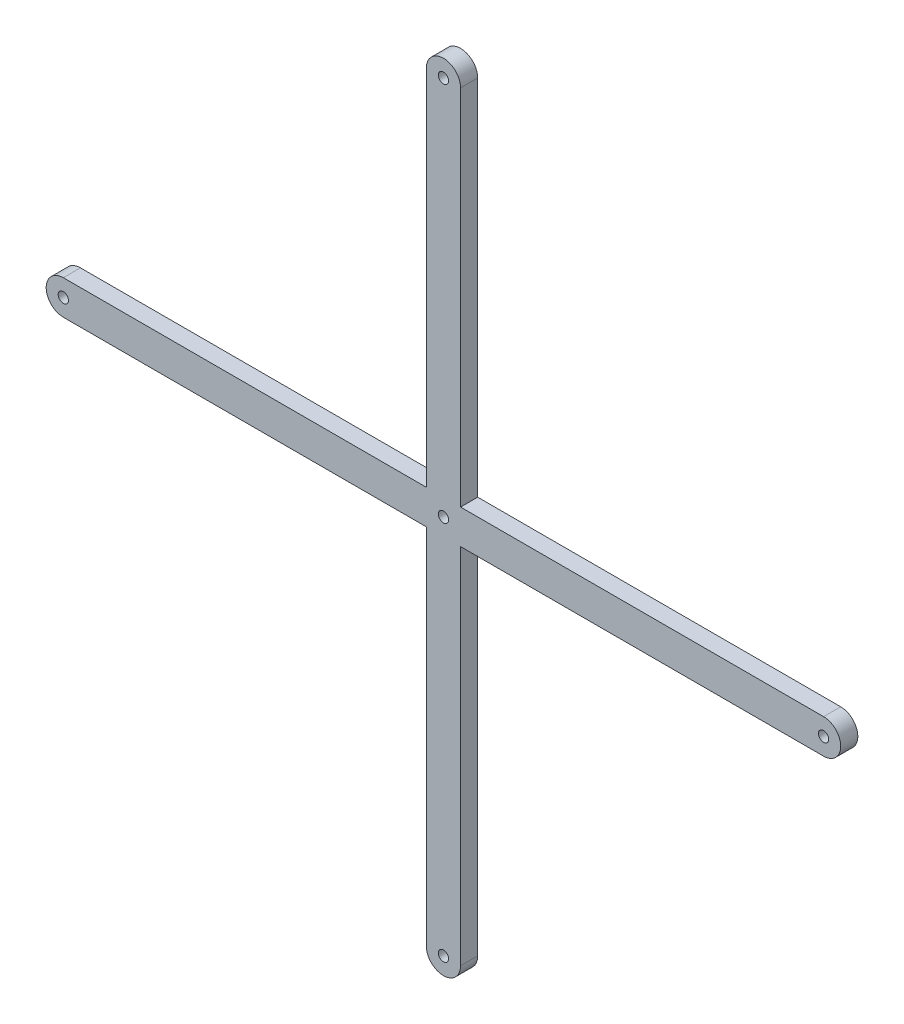
SolidWorks part; units mm, degrees
ref_plane "Front Plane" through (0, 0, 0) normal (0, 0, 1) x (1, 0, 0)
ref_plane "Top Plane" through (0, 0, 0) normal (0, 1, 0) x (1, 0, 0)
ref_plane "Right Plane" through (0, 0, 0) normal (1, 0, 0) x (0, 0, -1)
sketch "Sketch1" plane through (0, 0, 0) normal (0, 0, 1) x (1, 0, 0)
  line L0 (111, 0) -> (-111, 0) construction
  line L1 (5, -5) -> (5, -111)
  line L2 (-5, -5) -> (-5, -111)
  line L3 (0, 111) -> (0, -111) construction
  line L5 (-5, 5) -> (-111, 5)
  line L6 (-5, -5) -> (-111, -5)
  line L7 (5, 5) -> (5, 111)
  line L8 (-5, 5) -> (-5, 111)
  line L9 (5, -5) -> (111, -5)
  line L10 (5, 5) -> (111, 5)
  arc A1 (-5, -111) -> (5, -111) centre (0, -111) ccw
  circle A2 centre (0, 0) radius 1.5
  circle A3 centre (0, -111) radius 1.5
  arc A4 (-111, 5) -> (-111, -5) centre (-111, 0) ccw
  arc A5 (5, 111) -> (-5, 111) centre (0, 111) ccw
  arc A6 (111, -5) -> (111, 5) centre (111, 0) ccw
  circle A7 centre (-111, 0) radius 1.5
  circle A8 centre (0, 111) radius 1.5
  circle A9 centre (111, 0) radius 1.5
  point P3 (0, -55.5)
  point P34 (0, 0)
  point P37 (0, 0)
  dimension "D2" = 4
  dimension "D3" = 3
  dimension "D4" = 3
  dimension "D5" = 5
  dimension "D6" = 4
extrude "Boss-Extrude1" add sketch "Sketch1" along normal blind 5
